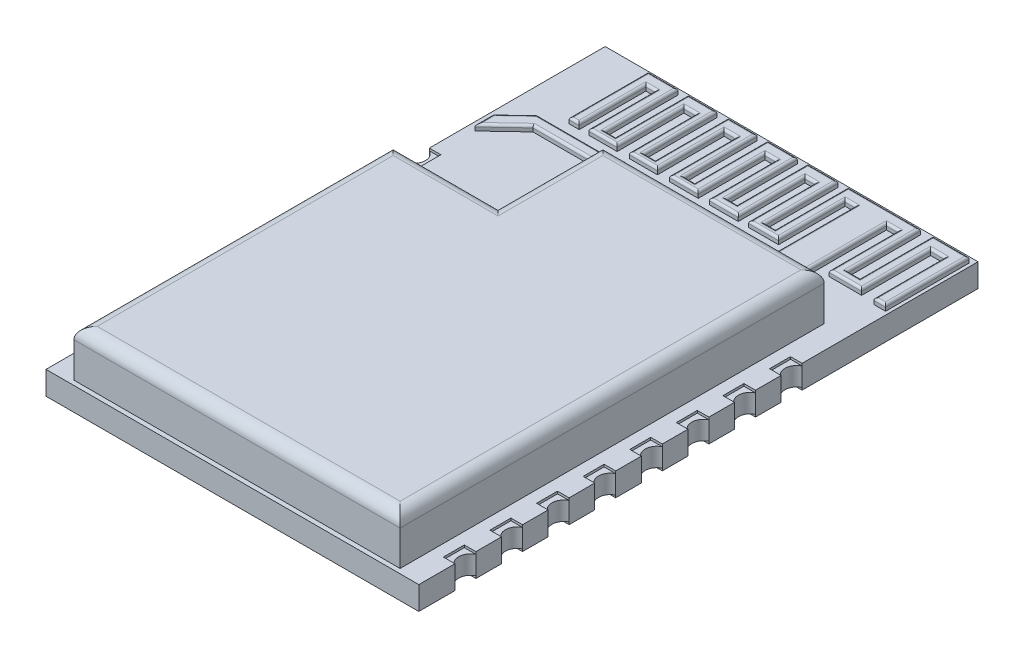
SolidWorks part; units mm, degrees
ref_plane "前基準面" through (0, 0, 0) normal (0, 0, 1) x (1, 0, 0)
ref_plane "上基準面" through (0, 0, 0) normal (0, 1, 0) x (1, 0, 0)
ref_plane "右基準面" through (0, 0, 0) normal (1, 0, 0) x (0, 0, -1)
sketch "草圖1" plane through (0, 0, 0) normal (0, 1, 0) x (1, 0, 0)
  line L5 (-8, 12) -> (8, 12)
  line L6 (-8, 12) -> (-8, -12)
  line L7 (-8, -12) -> (8, -12)
  line L8 (8, 12) -> (8, -12)
  line L9 (-8, 12) -> (8, -12) construction
  line L10 (-8, -12) -> (8, 12) construction
  point P0 (0, 0)
  dimension "D1" = 16
  dimension "24" = 24
extrude "填料-伸長1" add sketch "草圖1" along normal blind 1
sketch "草圖2" plane through (0, 1, 0) normal (0, 1, 0) x (1, 0, 0)
  line L0 (0, 0) -> (0, -5.3119)
  line L1 (-8.003, -9.55) -> (-7.503, -9.55)
  line L2 (-8.003, -9.55) -> (-8.003, -10.45)
  line L3 (-8.003, -10.45) -> (-7.503, -10.45)
  line L4 (-7.503, -9.55) -> (-7.503, -10.45)
  line L5 (8.003, -10.45) -> (7.503, -10.45)
  line L6 (7.503, -9.55) -> (7.503, -10.45)
  line L7 (8.003, -9.55) -> (7.503, -9.55)
  line L8 (8.003, -9.55) -> (8.003, -10.45)
  line L9 (-8.003, -7.55) -> (-8.003, -8.45)
  line L10 (-8.003, -7.55) -> (-7.503, -7.55)
  line L11 (-7.503, -7.55) -> (-7.503, -8.45)
  line L12 (-8.003, -8.45) -> (-7.503, -8.45)
  line L13 (-8.003, -5.55) -> (-8.003, -6.45)
  line L14 (-8.003, -5.55) -> (-7.503, -5.55)
  line L15 (-7.503, -5.55) -> (-7.503, -6.45)
  line L16 (-8.003, -6.45) -> (-7.503, -6.45)
  line L17 (-8.003, -3.55) -> (-8.003, -4.45)
  line L18 (-8.003, -3.55) -> (-7.503, -3.55)
  line L19 (-7.503, -3.55) -> (-7.503, -4.45)
  line L20 (-8.003, -4.45) -> (-7.503, -4.45)
  line L21 (-8.003, -1.55) -> (-8.003, -2.45)
  line L22 (-8.003, -1.55) -> (-7.503, -1.55)
  line L23 (-7.503, -1.55) -> (-7.503, -2.45)
  line L24 (-8.003, -2.45) -> (-7.503, -2.45)
  line L25 (-8.003, 0.45) -> (-8.003, -0.45)
  line L26 (-8.003, 0.45) -> (-7.503, 0.45)
  line L27 (-7.503, 0.45) -> (-7.503, -0.45)
  line L28 (-8.003, -0.45) -> (-7.503, -0.45)
  line L29 (-8.003, 2.45) -> (-8.003, 1.55)
  line L30 (-8.003, 2.45) -> (-7.503, 2.45)
  line L31 (-7.503, 2.45) -> (-7.503, 1.55)
  line L32 (-8.003, 1.55) -> (-7.503, 1.55)
  line L33 (-8.003, 4.45) -> (-8.003, 3.55)
  line L34 (-8.003, 4.45) -> (-7.503, 4.45)
  line L35 (-7.503, 4.45) -> (-7.503, 3.55)
  line L36 (-8.003, 3.55) -> (-7.503, 3.55)
  line L42 (8.003, -8.45) -> (7.503, -8.45)
  line L43 (7.503, -7.55) -> (7.503, -8.45)
  line L44 (8.003, -7.55) -> (7.503, -7.55)
  line L45 (8.003, -7.55) -> (8.003, -8.45)
  line L46 (8.003, -6.45) -> (7.503, -6.45)
  line L47 (7.503, -5.55) -> (7.503, -6.45)
  line L48 (8.003, -5.55) -> (7.503, -5.55)
  line L49 (8.003, -5.55) -> (8.003, -6.45)
  line L50 (8.003, -4.45) -> (7.503, -4.45)
  line L51 (7.503, -3.55) -> (7.503, -4.45)
  line L52 (8.003, -3.55) -> (7.503, -3.55)
  line L53 (8.003, -3.55) -> (8.003, -4.45)
  line L54 (8.003, -2.45) -> (7.503, -2.45)
  line L55 (7.503, -1.55) -> (7.503, -2.45)
  line L56 (8.003, -1.55) -> (7.503, -1.55)
  line L57 (8.003, -1.55) -> (8.003, -2.45)
  line L58 (8.003, -0.45) -> (7.503, -0.45)
  line L59 (7.503, 0.45) -> (7.503, -0.45)
  line L60 (8.003, 0.45) -> (7.503, 0.45)
  line L61 (8.003, 0.45) -> (8.003, -0.45)
  line L62 (8.003, 1.55) -> (7.503, 1.55)
  line L63 (7.503, 2.45) -> (7.503, 1.55)
  line L64 (8.003, 2.45) -> (7.503, 2.45)
  line L65 (8.003, 2.45) -> (8.003, 1.55)
  line L66 (8.003, 3.55) -> (7.503, 3.55)
  line L67 (7.503, 4.45) -> (7.503, 3.55)
  line L68 (8.003, 4.45) -> (7.503, 4.45)
  line L69 (8.003, 4.45) -> (8.003, 3.55)
  point P4 (-8.003, -10)
  line M6 (8, -12) -> (8, 12)
  line M8 (-8, 12) -> (-8, -12)
  dimension "D1" = 2
  dimension "D2" = 8
  dimension "D3" = 8
extrude "除料-伸長1" cut sketch "草圖2" against normal blind 0.1 contours L32 L31 L30 M8 | L28 L27 L26 M8 | L24 L23 L22 M8 | L20 L19 L18 M8 | L16 L15 L14 M8 | L12 L11 L10 M8 | L4 L1 L3 M8 | L7 L6 L5 M6 | L44 L43 L42 M6 | L48 L47 L46 M6 | L52 L51 L50 M6 | L56 L55 L54 M6 | L60 L59 L58 M6 | L68 L67 L66 M6 | L64 L63 L62 M6 | L35 L36 L33 L34
sketch "草圖3" plane through (0, 0, 0) normal (0, -1, 0) x (1, 0, 0)
  line L0 (7, 7.55) -> (7, 8.45)
  line L1 (8, 12) -> (8, -12) construction
  line L6 (7, 9.55) -> (8, 9.55)
  line L7 (7, 9.55) -> (7, 10.45)
  line L8 (7, 10.45) -> (8, 10.45)
  line L9 (8, 9.55) -> (8, 10.45)
  line L10 (-8, 12) -> (8, 12) construction
  line L11 (7, 7.55) -> (8, 7.55)
  line L12 (8, 7.55) -> (8, 8.45)
  line L13 (7, 8.45) -> (8, 8.45)
  line L14 (7, 5.55) -> (7, 6.45)
  line L15 (7, 5.55) -> (8, 5.55)
  line L16 (8, 5.55) -> (8, 6.45)
  line L17 (7, 6.45) -> (8, 6.45)
  line L18 (7, 3.55) -> (7, 4.45)
  line L19 (7, 3.55) -> (8, 3.55)
  line L20 (8, 3.55) -> (8, 4.45)
  line L21 (7, 4.45) -> (8, 4.45)
  line L22 (7, 1.55) -> (7, 2.45)
  line L23 (7, 1.55) -> (8, 1.55)
  line L24 (8, 1.55) -> (8, 2.45)
  line L25 (7, 2.45) -> (8, 2.45)
  line L26 (7, -0.45) -> (7, 0.45)
  line L27 (7, -0.45) -> (8, -0.45)
  line L28 (8, -0.45) -> (8, 0.45)
  line L29 (7, 0.45) -> (8, 0.45)
  line L30 (7, -2.45) -> (7, -1.55)
  line L31 (7, -2.45) -> (8, -2.45)
  line L32 (8, -2.45) -> (8, -1.55)
  line L33 (7, -1.55) -> (8, -1.55)
  line L34 (7, -4.45) -> (7, -3.55)
  line L35 (7, -4.45) -> (8, -4.45)
  line L36 (8, -4.45) -> (8, -3.55)
  line L37 (7, -3.55) -> (8, -3.55)
  line L38 (0, 0) -> (0, -2.1829)
  line L39 (-7, 10.45) -> (-8, 10.45)
  line L40 (-8, 9.55) -> (-8, 10.45)
  line L41 (-7, 9.55) -> (-8, 9.55)
  line L42 (-7, 9.55) -> (-7, 10.45)
  line L43 (-7, -4.45) -> (-8, -4.45)
  line L44 (-8, -4.45) -> (-8, -3.55)
  line L45 (-7, -3.55) -> (-8, -3.55)
  line L46 (-7, -4.45) -> (-7, -3.55)
  line L47 (-7, -2.45) -> (-8, -2.45)
  line L48 (-8, -2.45) -> (-8, -1.55)
  line L49 (-7, -1.55) -> (-8, -1.55)
  line L50 (-7, -2.45) -> (-7, -1.55)
  line L51 (-7, -0.45) -> (-8, -0.45)
  line L52 (-8, -0.45) -> (-8, 0.45)
  line L53 (-7, 0.45) -> (-8, 0.45)
  line L54 (-7, -0.45) -> (-7, 0.45)
  line L55 (-7, 1.55) -> (-8, 1.55)
  line L56 (-8, 1.55) -> (-8, 2.45)
  line L57 (-7, 2.45) -> (-8, 2.45)
  line L58 (-7, 1.55) -> (-7, 2.45)
  line L59 (-7, 3.55) -> (-8, 3.55)
  line L60 (-8, 3.55) -> (-8, 4.45)
  line L61 (-7, 4.45) -> (-8, 4.45)
  line L62 (-7, 3.55) -> (-7, 4.45)
  line L63 (-7, 5.55) -> (-8, 5.55)
  line L64 (-8, 5.55) -> (-8, 6.45)
  line L65 (-7, 6.45) -> (-8, 6.45)
  line L66 (-7, 5.55) -> (-7, 6.45)
  line L67 (-7, 7.55) -> (-8, 7.55)
  line L68 (-8, 7.55) -> (-8, 8.45)
  line L69 (-7, 8.45) -> (-8, 8.45)
  line L70 (-7, 7.55) -> (-7, 8.45)
  point P8 (8, 10)
  dimension "D1" = 2
  dimension "D2" = 0.9
  dimension "D3" = 8
extrude "除料-伸長2" cut sketch "草圖3" against normal blind 0.1 contours L67 L70 L69 L9 | L63 L66 L65 L9 | L59 L62 L61 L9 | L51 L54 L53 L9 | L47 L50 L49 L9 | L43 L46 L45 L9 | L33 L30 L31 L7 | L29 L26 L27 L7 | L25 L22 L23 L7 | L21 L18 L19 L7 | L13 L0 L11 L7 | L8 L7 L6 | L41 L40 L39 L42 | L58 L57 L56 L55 | L36 L37 L34 L35 | L17 L16 L15 L14
sketch "草圖8" plane through (0, 1, 0) normal (0, 1, 0) x (1, 0, 0)
  line L0 (-8, -12) -> (8, -12) construction
  line L1 (-1, 0.6) -> (3.7, 0.6)
  line L2 (-1, 0.6) -> (-1, -4.1)
  line L3 (-1, -4.1) -> (3.7, -4.1)
  line L4 (3.7, 0.6) -> (3.7, -4.1)
  line L5 (-1, 0.6) -> (3.7, -4.1) construction
  line L6 (-1, -4.1) -> (3.7, 0.6) construction
  line L7 (-8, -2.45) -> (-8, -3.55) construction
  point P0 (1.35, -1.75)
  dimension "D1" = 7.9
  dimension "D2" = 7
  dimension "D3" = 4.7
  dimension "D4" = 4.7
extrude "除料-伸長3" cut sketch "草圖8" against normal blind 0.1
sketch "草圖12" plane through (0, 0.9, 0) normal (0, 1, 0) x (1, 0, 0)
  line L0 (-1, 0.6) -> (-1, -4.1) construction
  line L1 (-1, -4.1) -> (3.7, -4.1) construction
  circle A1 centre (-0.51, -3.65) radius 0.2
  circle A2 centre (0.42, -3.65) radius 0.2
  circle A3 centre (1.35, -3.65) radius 0.2
  circle A4 centre (2.28, -3.65) radius 0.2
  circle A5 centre (3.21, -3.65) radius 0.2
  circle A6 centre (-0.51, -2.72) radius 0.2
  circle A7 centre (0.42, -2.72) radius 0.2
  circle A8 centre (1.35, -2.72) radius 0.2
  circle A9 centre (2.28, -2.72) radius 0.2
  circle A10 centre (3.21, -2.72) radius 0.2
  circle A11 centre (-0.51, -1.79) radius 0.2
  circle A12 centre (0.42, -1.79) radius 0.2
  circle A13 centre (1.35, -1.79) radius 0.2
  circle A14 centre (2.28, -1.79) radius 0.2
  circle A15 centre (3.21, -1.79) radius 0.2
  circle A16 centre (-0.51, -0.86) radius 0.2
  circle A17 centre (0.42, -0.86) radius 0.2
  circle A18 centre (1.35, -0.86) radius 0.2
  circle A19 centre (2.28, -0.86) radius 0.2
  circle A20 centre (3.21, -0.86) radius 0.2
  circle A21 centre (-0.51, 0.07) radius 0.2
  circle A22 centre (0.42, 0.07) radius 0.2
  circle A23 centre (1.35, 0.07) radius 0.2
  circle A24 centre (2.28, 0.07) radius 0.2
  circle A25 centre (3.21, 0.07) radius 0.2
  dimension "D1" = 0.49
  dimension "D2" = 0.45
  dimension "D3" = 5
  dimension "D4" = 5
extrude "除料-伸長4" cut sketch "草圖12" against normal blind 0.1
sketch "草圖13" plane through (0, 1, 0) normal (0, 1, 0) x (1, 0, 0)
  line L5 (-1, 0.6) -> (3.7, 0.6)
  line L6 (-1, 0.6) -> (-1, -4.1)
  line L7 (-1, -4.1) -> (3.7, -4.1)
  line L8 (3.7, 0.6) -> (3.7, -4.1)
extrude "填料-伸長2" add sketch "草圖13" against normal blind 0.5
sketch "草圖15" plane through (0, 0, 0) normal (0, -1, 0) x (1, 0, 0)
  line L0 (-8, 12) -> (8, 12) construction
  line L1 (1, -0.6) -> (-3.7, -0.6)
  line L2 (1, -0.6) -> (1, 4.1)
  line L3 (1, 4.1) -> (-3.7, 4.1)
  line L4 (-3.7, -0.6) -> (-3.7, 4.1)
  line L5 (1, -0.6) -> (-3.7, 4.1) construction
  line L6 (1, 4.1) -> (-3.7, -0.6) construction
  line L7 (8, 1.55) -> (8, 0.45) construction
  point P0 (-1.35, 1.75)
  point P9 (8, 1)
  dimension "D1" = 7.9
  dimension "D2" = 7
  dimension "D3" = 4.7
  dimension "D4" = 4.7
extrude "除料-伸長5" cut sketch "草圖15" against normal blind 0.1
sketch "草圖16" plane through (0, 0, 0) normal (0, -1, 0) x (1, 0, 0)
  line L0 (1, 4.1) -> (-3.7, 4.1) construction
  line L1 (1, -0.6) -> (1, 4.1) construction
  circle A0 centre (0.51, 3.61) radius 0.2
  circle A1 centre (-0.42, 3.61) radius 0.2
  circle A2 centre (-1.35, 3.61) radius 0.2
  circle A3 centre (-2.28, 3.61) radius 0.2
  circle A4 centre (-3.21, 3.61) radius 0.2
  circle A5 centre (-3.21, 2.68) radius 0.2
  circle A6 centre (-2.28, 2.68) radius 0.2
  circle A7 centre (-1.35, 2.68) radius 0.2
  circle A8 centre (-0.42, 2.68) radius 0.2
  circle A9 centre (0.51, 2.68) radius 0.2
  circle A10 centre (-3.21, 1.75) radius 0.2
  circle A11 centre (-2.28, 1.75) radius 0.2
  circle A12 centre (-1.35, 1.75) radius 0.2
  circle A13 centre (-0.42, 1.75) radius 0.2
  circle A14 centre (0.51, 1.75) radius 0.2
  circle A15 centre (-3.21, 0.82) radius 0.2
  circle A16 centre (-2.28, 0.82) radius 0.2
  circle A17 centre (-1.35, 0.82) radius 0.2
  circle A18 centre (-0.42, 0.82) radius 0.2
  circle A19 centre (0.51, 0.82) radius 0.2
  circle A20 centre (-3.21, -0.11) radius 0.2
  circle A21 centre (-2.28, -0.11) radius 0.2
  circle A22 centre (-1.35, -0.11) radius 0.2
  circle A23 centre (-0.42, -0.11) radius 0.2
  circle A24 centre (0.51, -0.11) radius 0.2
  dimension "D1" = 0.49
  dimension "D2" = 0.49
  dimension "D3" = 5
  dimension "D4" = 5
extrude "除料-伸長6" cut sketch "草圖16" against normal blind 0.25
sketch "草圖17" plane through (0, 1, 0) normal (0, 1, 0) x (1, 0, 0)
  line L0 (-8, -12) -> (8, -12) construction
  line L5 (-2.5, 6.4) -> (7, 6.4)
  line L6 (-7, 1.4) -> (-7, -10.8)
  line L7 (-7, -10.8) -> (7, -10.8)
  line L8 (7, 6.4) -> (7, -10.8)
  line L9 (-8, 12) -> (-8, 4.45) construction
  line L10 (8, 4.45) -> (8, 12) construction
  line L16 (-2.5, 6.4) -> (-2.5, 1.9)
  line L17 (-2.5, 1.9) -> (-7, 1.9)
  line L18 (-7, 1.9) -> (-7, 1.4)
  dimension "D1" = 1.2
  dimension "D2" = 1
  dimension "D3" = 1
extrude "填料-伸長4" add sketch "草圖17" along normal blind 2
sketch "草圖18" plane through (0, 1, 0) normal (0, 1, 0) x (1, 0, 0)
  line L1 (-8, 4.45) -> (-8, 3.55)
  line L3 (-8, 2.45) -> (-8, 1.55)
  line L4 (-8, 0.45) -> (-8, -0.45)
  line L5 (-8, -1.55) -> (-8, -2.45)
  line L6 (-8, -3.55) -> (-8, -4.45)
  line L7 (-8, -5.55) -> (-8, -6.45)
  line L8 (-8, -7.55) -> (-8, -8.45)
  line L9 (-8, -9.55) -> (-8, -10.45)
  line L12 (8, 4.45) -> (8, 3.55)
  line L13 (8, 2.45) -> (8, 1.55)
  line L14 (8, 0.45) -> (8, -0.45)
  line L15 (8, -1.55) -> (8, -2.45)
  line L16 (8, -3.55) -> (8, -4.45)
  line L17 (8, -5.55) -> (8, -6.45)
  line L18 (8, -7.55) -> (8, -8.45)
  line L19 (8, -9.55) -> (8, -10.45)
  arc A0 (-8, 4.45) -> (-8, 3.55) centre (-8.2179, 4) cw
  arc A1 (-8, 2.45) -> (-8, 1.55) centre (-8.2179, 2) cw
  arc A2 (-8, 0.45) -> (-8, -0.45) centre (-8.2179, 0) cw
  arc A3 (-8, -1.55) -> (-8, -2.45) centre (-8.2179, -2) cw
  arc A4 (-8, -3.55) -> (-8, -4.45) centre (-8.2179, -4) cw
  arc A5 (-8, -5.55) -> (-8, -6.45) centre (-8.2179, -6) cw
  arc A6 (-8, -7.55) -> (-8, -8.45) centre (-8.2179, -8) cw
  arc A7 (-8, -9.55) -> (-8, -10.45) centre (-8.2179, -10) cw
  arc A8 (8, 4.45) -> (8, 3.55) centre (8.2179, 4) ccw
  arc A9 (8, 2.45) -> (8, 1.55) centre (8.2179, 2) ccw
  arc A10 (8, 0.45) -> (8, -0.45) centre (8.2179, 0) ccw
  arc A11 (8, -1.55) -> (8, -2.45) centre (8.2179, -2) ccw
  arc A12 (8, -3.55) -> (8, -4.45) centre (8.2179, -4) ccw
  arc A13 (8, -5.55) -> (8, -6.45) centre (8.2179, -6) ccw
  arc A14 (8, -7.55) -> (8, -8.45) centre (8.2179, -8) ccw
  arc A15 (8, -9.55) -> (8, -10.45) centre (8.2179, -10) ccw
  dimension "D1" = 8
extrude "除料-伸長7" cut sketch "草圖18" against normal blind 2
sketch "草圖19" plane through (0, 1, 0) normal (0, 1, 0) x (1, 0, 0)
  line L0 (-144.5969, 121.1687) -> (-19.9302, 121.1687) construction
  line L1 (-7, -10.8) -> (-7, -11.8025)
  line L2 (-7, -11.8025) -> (7, -11.8025)
  line L3 (7, -10.8) -> (7, -11.8025)
  line L4 (7, -10.8) -> (7, -11.8025)
  line L5 (-7, -10.8) -> (7, -10.8)
extrude "填料-伸長5" add sketch "草圖19" along normal up to surface (2 mm away) contours L5 L1 L2 L3 up to face at (-0.8333, 3, 0.8333)
sketch "草圖20" plane through (0, 1, 0) normal (0, 1, 0) x (1, 0, 0)
  line L0 (23.4441, 125.3473) -> (148.1108, 125.3473) construction
  line L1 (2.7746, 7.2994) -> (2.7746, 6.4)
  line L3 (7, 6.4) -> (-2.5, 6.4) construction
  line L4 (2.7746, 7.2994) -> (4.8557, 7.2994)
  line L5 (4.8557, 7.2994) -> (4.8557, 11.2142)
  line L6 (4.8557, 11.2142) -> (5.3615, 11.2142)
  line L7 (5.3615, 11.2142) -> (5.3615, 8.253)
  line L8 (5.3615, 8.253) -> (6.7537, 8.253)
  line L9 (6.7537, 8.253) -> (6.7537, 11.2142)
  line L10 (6.7537, 11.2142) -> (7.3504, 11.2142)
  line L11 (7.3504, 11.2142) -> (7.3504, 8.1756)
  line L12 (7.3504, 8.1756) -> (7.8586, 8.1756)
  line L13 (7.8586, 8.1756) -> (7.8586, 11.7556)
  line L14 (7.8586, 11.7556) -> (6.3117, 11.7556)
  line L15 (6.3117, 11.7556) -> (6.3117, 8.6286)
  line L16 (6.3117, 8.6286) -> (5.8587, 8.6286)
  line L17 (5.8587, 8.6286) -> (5.7703, 8.6286)
  line L18 (5.7703, 8.6286) -> (5.7703, 11.7556)
  line L19 (5.7703, 11.7556) -> (2.6765, 11.7556)
  line L20 (2.6765, 11.7556) -> (2.6765, 8.6286)
  line L21 (2.6765, 8.6286) -> (2.2345, 8.6286)
  line L22 (2.2345, 8.6286) -> (2.2345, 11.7556)
  line L23 (2.2345, 11.7556) -> (0.9417, 11.7556)
  line L24 (0.9417, 11.7556) -> (0.9417, 8.7281)
  line L25 (0.9417, 8.7281) -> (0.4887, 8.7281)
  line L26 (0.4887, 8.7281) -> (0.4887, 11.7556)
  line L27 (0.4887, 11.7556) -> (-0.782, 11.7556)
  line L28 (-0.782, 11.7556) -> (-0.782, 8.6286)
  line L29 (-0.782, 8.6286) -> (-1.235, 8.6286)
  line L30 (-1.235, 8.6286) -> (-1.235, 11.7556)
  line L31 (-1.235, 11.7556) -> (-2.4725, 11.7556)
  line L32 (-2.4725, 11.7556) -> (-2.4725, 8.6286)
  line L33 (-2.4725, 8.6286) -> (-2.9587, 8.6286)
  line L34 (-2.9587, 8.6286) -> (-2.9587, 11.7556)
  line L35 (-2.9587, 11.7556) -> (-4.1852, 11.7556)
  line L36 (-4.1852, 11.7556) -> (-4.1852, 8.6286)
  line L37 (-4.1852, 8.6286) -> (-4.6323, 8.6286)
  line L38 (-4.6323, 8.6286) -> (-4.6323, 11.7556)
  line L39 (-4.6323, 11.7556) -> (-5.9045, 11.7556)
  line L40 (-5.9045, 11.7556) -> (-5.9045, 8.3512)
  line L41 (-5.9045, 8.3512) -> (-5.4695, 8.3512)
  line L42 (-5.4695, 8.3512) -> (-5.4695, 11.2142)
  line L43 (-5.4695, 11.2142) -> (-5.0563, 11.2142)
  line L44 (-5.0563, 11.2142) -> (-5.0563, 8.3512)
  line L45 (-5.0563, 8.3512) -> (-3.8385, 8.3512)
  line L46 (-3.8385, 8.3512) -> (-3.8385, 11.2142)
  line L47 (-3.8385, 11.2142) -> (-3.3166, 11.2142)
  line L48 (-3.3166, 11.2142) -> (-3.3166, 8.3512)
  line L49 (-3.3166, 8.3512) -> (-2.1096, 8.3512)
  line L50 (-2.1096, 8.3512) -> (-2.1096, 11.2142)
  line L51 (-2.1096, 11.2142) -> (-1.5877, 11.2142)
  line L52 (-1.5877, 11.2142) -> (-1.5877, 8.3512)
  line L53 (-1.5877, 8.3512) -> (-0.3589, 8.3512)
  line L54 (-0.3589, 8.3512) -> (-0.3589, 11.2142)
  line L55 (-0.3589, 11.2142) -> (0.1195, 11.2142)
  line L56 (0.1195, 11.2142) -> (0.1195, 8.3512)
  line L57 (0.1195, 8.3512) -> (1.3591, 8.3512)
  line L58 (1.3591, 8.3512) -> (1.3591, 11.2142)
  line L59 (1.3591, 11.2142) -> (1.8049, 11.2142)
  line L60 (1.8049, 11.2142) -> (1.8049, 8.3512)
  line L61 (1.8049, 8.3512) -> (3.088, 8.3512)
  line L62 (3.088, 8.3512) -> (3.088, 11.2142)
  line L63 (3.088, 11.2142) -> (3.523, 11.2142)
  line L64 (3.523, 11.2142) -> (3.523, 7.764)
  line L65 (3.523, 7.764) -> (-6.6874, 7.764)
  line L66 (-6.6874, 7.764) -> (-7.6552, 6.8497)
  line L67 (-7.6552, 6.8497) -> (-7.6552, 6.1428)
  line L68 (-6.3743, 7.2733) -> (2.2333, 7.2733)
  line L69 (2.2333, 7.2733) -> (2.25, 6.4)
  line L70 (-6.3743, 7.2733) -> (-7.5709, 6.1428)
  line L71 (7, 6.4) -> (-2.5, 6.4) construction
  line L72 (2.25, 6.4) -> (2.7746, 6.4)
  line L73 (-7.6552, 6.1428) -> (-7.6552, 6.0749)
  line L75 (-7.5709, 6.1428) -> (-7.6552, 6.0632)
  line L76 (-7.6552, 6.0632) -> (-7.6552, 6.0749)
ref_plane "平面1" through (8, 1, -4.45) normal (0, 0, -1) x (-1, 0, 0)
extrude "填料-伸長7" add sketch "草圖20" along normal blind 0.25 contours L65 L66 L67 L73 L76 L75 L70 L68 L69 L72 L1 L4 L5 L6 L7 L8 L9 L10 L11 L12 L13 L14 L15 L16 L17 L18 L19 L20 L21 L22 L23 L24 L25 L26 L27 L28 L29 L30 L31 L32 L33 L34 L35 L36 L37 L38 L39 L40 L41 L42 L43 L44 L45 L46 L47 L48 L49 L50 L51 L52 L53 L54 L55 L56 L57 L58 L59 L60 L61 L62 L63 L64
fillet "圓角4" radius 0.1 70 edges at (2.7746, 1.125, -6.4) (2.25, 1.125, -6.4) (3.3055, 1.25, -11.2142) (3.088, 1.25, -9.7827) (2.4465, 1.25, -8.3512) (1.8049, 1.25, -9.7827) (1.582, 1.25, -11.2142) (1.3591, 1.25, -9.7827) (0.7393, 1.25, -8.3512) (0.1195, 1.25, -9.7827) (-0.1197, 1.25, -11.2142) (-0.3589, 1.25, -9.7827) (-0.9733, 1.25, -8.3512) (-1.5877, 1.25, -9.7827) (-1.8486, 1.25, -11.2142) (-2.1096, 1.25, -9.7827) (-2.7131, 1.25, -8.3512) (-3.3166, 1.25, -9.7827) (-3.5775, 1.25, -11.2142) (-3.8385, 1.25, -9.7827) (-4.4474, 1.25, -8.3512) (-5.0563, 1.25, -9.7827) (-5.2629, 1.25, -11.2142) (-5.4695, 1.25, -9.7827) (-5.687, 1.25, -8.3512) (-5.9045, 1.25, -10.0534) (-5.2684, 1.25, -11.7556) (-4.6323, 1.25, -10.1921) (-4.4087, 1.25, -8.6286) (-4.1852, 1.25, -10.1921) (-3.572, 1.25, -11.7556) (-2.9587, 1.25, -10.1921) (-2.7156, 1.25, -8.6286) (-2.4725, 1.25, -10.1921) (-1.8538, 1.25, -11.7556) (-1.235, 1.25, -10.1921) (-1.0085, 1.25, -8.6286) (-0.782, 1.25, -10.1921) (-0.1466, 1.25, -11.7556) (0.4887, 1.25, -10.2418) (0.7152, 1.25, -8.7281) (0.9417, 1.25, -10.2418) (1.5881, 1.25, -11.7556) (2.2345, 1.25, -10.1921) (2.4555, 1.25, -8.6286) (2.6765, 1.25, -10.1921) (4.2234, 1.25, -11.7556) (5.7703, 1.25, -10.1921) (6.041, 1.25, -8.6286) (6.3117, 1.25, -10.1921) (7.0852, 1.25, -11.7556) (7.8586, 1.25, -9.9656) (7.6045, 1.25, -8.1756) (7.3504, 1.25, -9.6949) (7.052, 1.25, -11.2142) (6.7537, 1.25, -9.7336) (6.0576, 1.25, -8.253) (5.3615, 1.25, -9.7336) (5.1086, 1.25, -11.2142) (4.8557, 1.25, -9.2568) (3.8151, 1.25, -7.2994) (2.7746, 1.25, -6.8497) (2.5123, 1.25, -6.4) (2.2417, 1.25, -6.8367) (-2.0705, 1.25, -7.2733) (-7.0147, 1.25, -6.6683) (-7.6552, 1.25, -6.4565) (-7.1713, 1.25, -7.3069) (-1.5822, 1.25, -7.764) (3.523, 1.25, -9.4891)
fillet "圓角5" radius 0.5 6 edges at (0, 3, 11.8025) (-7, 3, 4.9512) (-4.75, 3, -1.9) (-2.5, 3, -4.15) (2.25, 3, -6.4) (7, 3, 2.7012)
